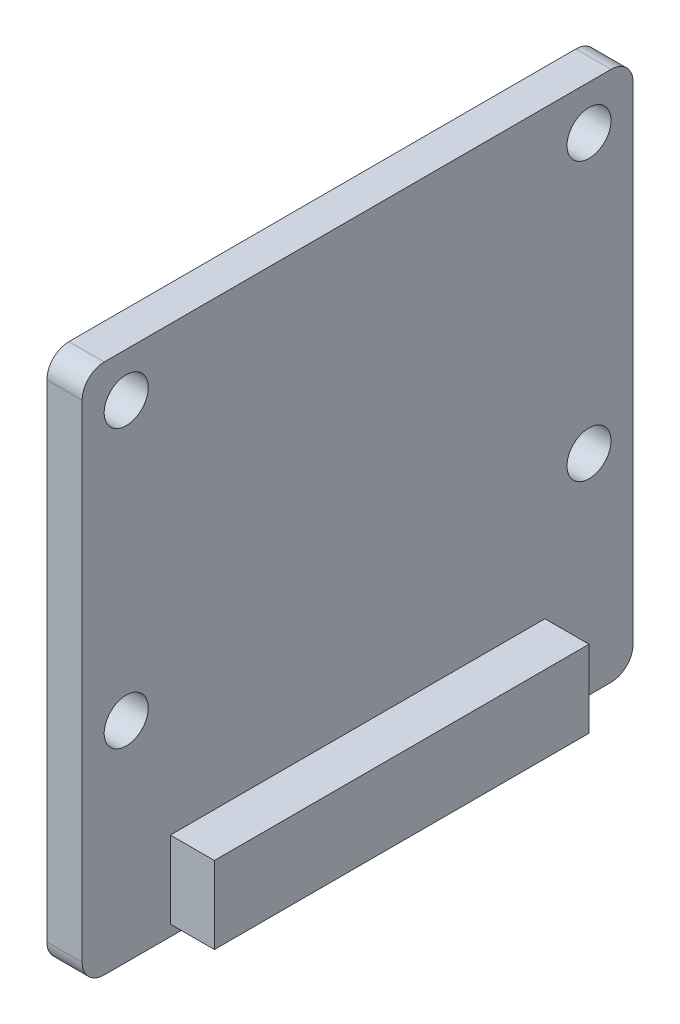
SolidWorks part; units mm, degrees
ref_plane "Ön Düzlem" through (0, 0, 0) normal (0, 0, 1) x (1, 0, 0)
ref_plane "Üst Düzlem" through (0, 0, 0) normal (0, 1, 0) x (1, 0, 0)
ref_plane "Sağ Düzlem" through (0, 0, 0) normal (1, 0, 0) x (0, 0, -1)
ref_plane "Düzlem1" through (1.6, 0, 0) normal (1, 0, 0) x (0, 0, -1)
sketch "Çizim1" plane through (1.6, 0, 0) normal (1, 0, 0) x (0, 0, -1)
  line L0 (-12.5, 6.59) -> (-12.5, -17.5)
  line L1 (-12.5, -17.5) -> (12.5, -17.5)
  line L2 (12.5, -17.5) -> (12.5, 6.59)
  line L3 (12.5, 6.59) -> (-12.5, 6.59)
extrude "Yükseklik-Ekstrüzyon1" add sketch "Çizim1" against normal blind 1.6
sketch "Çizim2" plane through (1.6, 0, 0) normal (1, 0, 0) x (0, 0, -1)
  line L0 (-8.5, -17) -> (-8.5, -13.5)
  line L1 (-8.5, -13.5) -> (8.5, -13.5)
  line L2 (8.5, -13.5) -> (8.5, -17)
  line L3 (8.5, -17) -> (-8.5, -17)
extrude "Yükseklik-Ekstrüzyon2" add sketch "Çizim2" along normal blind 2
fillet "Radyus1" radius 1 4 edges at (0.8, -17.5, 12.5) (0.8, 6.59, 12.5) (0.8, -17.5, -12.5) (0.8, 6.59, -12.5)
sketch "Çizim5" plane through (1.6, 0, 0) normal (1, 0, 0) x (0, 0, -1)
  line L0 (-11.5, -17.5) -> (11.5, -17.5) construction
  line L1 (11.5, 6.59) -> (-11.5, 6.59) construction
  line L2 (-12.5, 5.59) -> (-12.5, -16.5) construction
  line L3 (12.5, -16.5) -> (12.5, 5.59) construction
  circle A0 centre (10.5, 4.59) radius 1
  circle A1 centre (-10.5, 4.59) radius 1
  circle A2 centre (-10.5, -8) radius 1
  circle A3 centre (10.5, -8) radius 1
  dimension "D1" = 2
  dimension "D2" = 2
  dimension "D3" = 2
  dimension "D4" = 2
  dimension "D5" = 2
  dimension "D6" = 2
  dimension "D7" = 2
  dimension "D8" = 9.5
extrude "Kes-Ekstrüzyon1" cut sketch "Çizim5" against normal blind 10
